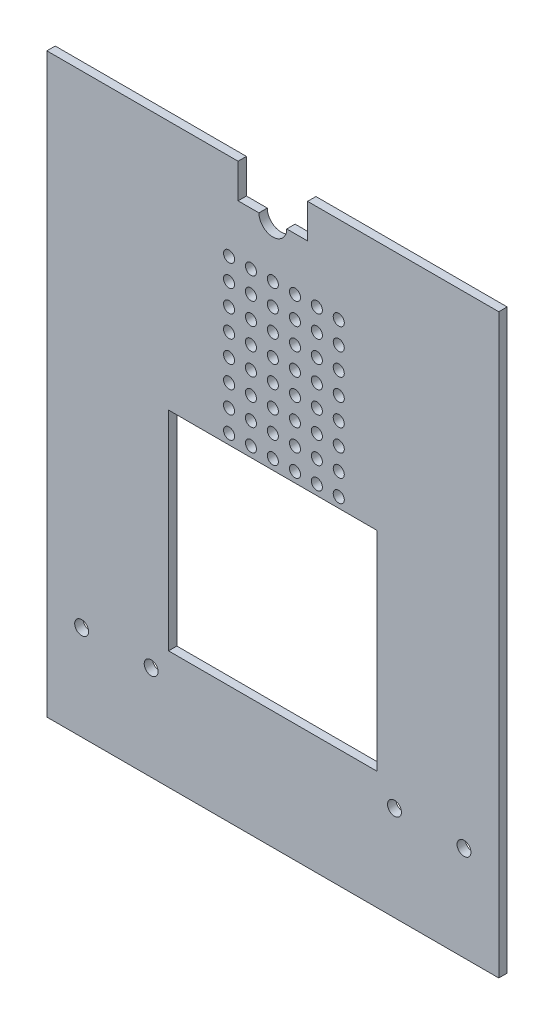
SolidWorks part; units mm, degrees
ref_plane "Front Plane" through (0, 0, 0) normal (0, 0, 1) x (1, 0, 0)
ref_plane "Top Plane" through (0, 0, 0) normal (0, 1, 0) x (1, 0, 0)
ref_plane "Right Plane" through (0, 0, 0) normal (1, 0, 0) x (0, 0, -1)
sketch "Sketch1" plane through (0, 0, 0) normal (0, 0, 1) x (1, 0, 0)
  line L1 (-82.55, 146.05) -> (82.55, 146.05)
  line L2 (-82.55, 146.05) -> (-82.55, -146.05)
  line L3 (-82.55, -146.05) -> (82.55, -146.05)
  line L4 (82.55, 146.05) -> (82.55, -146.05)
  line L5 (-82.55, 146.05) -> (82.55, -146.05) construction
  line L6 (-82.55, -146.05) -> (82.55, 146.05) construction
  point P0 (0, 0)
  dimension "D1" = 165.1
  dimension "D2" = 292.1
extrude "Boss-Extrude1" add sketch "Sketch1" along normal blind 3.048
sketch "Sketch2" plane through (0, 0, 0) normal (0, 0, 1) x (1, 0, 0)
  line L1 (-82.55, -146.05) -> (82.55, -146.05) construction
  line L2 (-82.55, -146.05) -> (82.55, -146.05) construction
  line L3 (8.0869, 109.0549) -> (-8.0869, 109.0549)
  line L4 (8.0869, 109.0549) -> (8.0869, 76.3651)
  line L5 (8.0869, 76.3651) -> (-8.0869, 76.3651)
  line L6 (-8.0869, 109.0549) -> (-8.0869, 76.3651)
  line L7 (8.0869, 109.0549) -> (-8.0869, 76.3651) construction
  line L8 (8.0869, 76.3651) -> (-8.0869, 109.0549) construction
  line L9 (-38.1, -21.59) -> (38.1, -21.59)
  line L10 (-38.1, -21.59) -> (-38.1, -97.79)
  line L11 (-38.1, -97.79) -> (38.1, -97.79)
  line L12 (38.1, -21.59) -> (38.1, -97.79)
  line L13 (-38.1, -21.59) -> (38.1, -97.79) construction
  line L14 (-38.1, -97.79) -> (38.1, -21.59) construction
  circle A1 centre (0, 92.71) radius 10.7315
  circle A2 centre (0, 38.1) radius 2.0193
  circle A3 centre (0, 30.1) radius 2.0193
  circle A4 centre (0, 22.1) radius 2.0193
  circle A5 centre (0, 14.1) radius 2.0193
  circle A6 centre (0, 6.1) radius 2.0193
  circle A7 centre (0, -1.9) radius 2.0193
  circle A8 centre (0, -9.9) radius 2.0193
  circle A9 centre (0, -17.9) radius 2.0193
  circle A10 centre (-8, 38.1) radius 2.0193
  circle A11 centre (-16, 38.1) radius 2.0193
  circle A12 centre (-8, 30.1) radius 2.0193
  circle A13 centre (-16, 30.1) radius 2.0193
  circle A14 centre (-8, 22.1) radius 2.0193
  circle A15 centre (-16, 22.1) radius 2.0193
  circle A16 centre (-8, 14.1) radius 2.0193
  circle A17 centre (-16, 14.1) radius 2.0193
  circle A18 centre (-8, 6.1) radius 2.0193
  circle A19 centre (-16, 6.1) radius 2.0193
  circle A20 centre (-8, -1.9) radius 2.0193
  circle A21 centre (-16, -1.9) radius 2.0193
  circle A22 centre (-8, -9.9) radius 2.0193
  circle A23 centre (-16, -9.9) radius 2.0193
  circle A24 centre (-8, -17.9) radius 2.0193
  circle A25 centre (-16, -17.9) radius 2.0193
  circle A26 centre (24.0869, 14.1) radius 2.0193
  circle A27 centre (8.0869, 14.1) radius 2.0193
  circle A28 centre (8.0869, -17.9) radius 2.0193
  circle A29 centre (24.0869, 6.1) radius 2.0193
  circle A30 centre (16.0869, 6.1) radius 2.0193
  circle A31 centre (8.0869, -1.9) radius 2.0193
  circle A32 centre (8.0869, 30.1) radius 2.0193
  circle A33 centre (24.0869, 22.1) radius 2.0193
  circle A34 centre (24.0869, -1.9) radius 2.0193
  circle A35 centre (24.0869, -9.9) radius 2.0193
  circle A36 centre (8.0869, 6.1) radius 2.0193
  circle A37 centre (16.0869, 22.1) radius 2.0193
  circle A38 centre (8.0869, 22.1) radius 2.0193
  circle A39 centre (8.0869, -9.9) radius 2.0193
  circle A40 centre (24.0869, -17.9) radius 2.0193
  circle A41 centre (16.0869, 14.1) radius 2.0193
  circle A42 centre (16.0869, -17.9) radius 2.0193
  circle A43 centre (16.0869, 30.1) radius 2.0193
  circle A44 centre (24.0869, 30.1) radius 2.0193
  circle A45 centre (16.0869, -9.9) radius 2.0193
  circle A46 centre (16.0869, -1.9) radius 2.0193
  circle A47 centre (16.0869, 38.1) radius 2.0193
  circle A48 centre (8.0869, 38.1) radius 2.0193
  circle A49 centre (24.0869, 38.1) radius 2.0193
  point P2 (0, -59.69)
  dimension "D3" = 21.463
  dimension "D5" = 4.0386
  dimension "D7" = 184.15
  dimension "D2" = 86.36
  dimension "D4" = 152.4
  dimension "D8" = 16.1738
  dimension "D9" = 32.6898
  dimension "D11" = 76.2
  dimension "D12" = 76.2
  dimension "D6" = 3
  dimension "D10" = 8
extrude "Cut-Extrude1" cut sketch "Sketch2" along normal through all contours A13 | A19 | A18 | A20 | A24 | A39 | A31
sketch "Sketch4" plane through (0, 0, 0) normal (0, 0, 1) x (1, 0, 0)
  line L0 (-12.7, 57.3108) -> (-12.7, 69.85)
  line L1 (82.55, 146.05) -> (-82.55, 146.05)
  line L2 (82.55, 146.05) -> (82.55, 69.85)
  line L4 (-82.55, 146.05) -> (-82.55, 69.85)
  line L7 (-12.7, 57.3108) -> (12.7, 57.3108)
  line L9 (12.7, 57.3108) -> (12.7, 69.85)
  line L10 (-82.55, 69.85) -> (-12.7, 69.85)
  line L11 (12.7, 69.85) -> (82.55, 69.85)
  point P5 (0, 146.05)
  dimension "D1" = 165.1
  dimension "D2" = 76.2
  dimension "D3" = 25.4
  dimension "D4" = 69.85
extrude "Cut-Extrude2" cut sketch "Sketch4" along normal through all
sketch "Sketch5" plane through (0, 0, 0) normal (0, 0, -1) x (-1, 0, 0)
  line L0 (82.55, -146.05) -> (-82.55, -146.05) construction
  line L1 (-82.55, -146.05) -> (-82.55, 69.85) construction
  line L2 (0, 1.6764) -> (0, -1.6764) construction
  circle A0 centre (-44.45, -106.299) radius 2.54
  circle A2 centre (-69.85, -106.299) radius 2.54
  circle A3 centre (69.85, -106.299) radius 2.54
  circle A4 centre (44.45, -106.299) radius 2.54
  dimension "D1" = 5.08
  dimension "D2" = 39.751
  dimension "D3" = 25.4
  dimension "D4" = 12.7
extrude "Cut-Extrude3" cut sketch "Sketch5" against normal through all
sketch "Sketch6" plane through (0, 0, 0) normal (0, 0, -1) x (-1, 0, 0)
  line L0 (82.55, 69.85) -> (82.55, -146.05) construction
  line L1 (-82.55, -146.05) -> (82.55, -146.05)
  line L2 (-82.55, -146.05) -> (-82.55, -140.97)
  line L3 (-82.55, -140.97) -> (82.55, -140.97)
  line L4 (82.55, -146.05) -> (82.55, -140.97)
  dimension "D1" = 5.08
extrude "Cut-Extrude4" cut sketch "Sketch6" against normal through all
sketch "Sketch7" plane through (0, 0, 3.048) normal (0, 0, 1) x (1, 0, 0)
  line L0 (-12.7, 57.3108) -> (12.7, 57.3108) construction
  circle A0 centre (0, 57.3108) radius 5.08
  dimension "D1" = 10.16
extrude "Cut-Extrude5" cut sketch "Sketch7" against normal up to next
equation "\"thickness_acrylic0.1\"=0.1in"
equation "\"motor offset\"=6mm"
equation "\"thickness0.25\"=0.225in"
equation "\"thickness0.125\"=0.122in"
